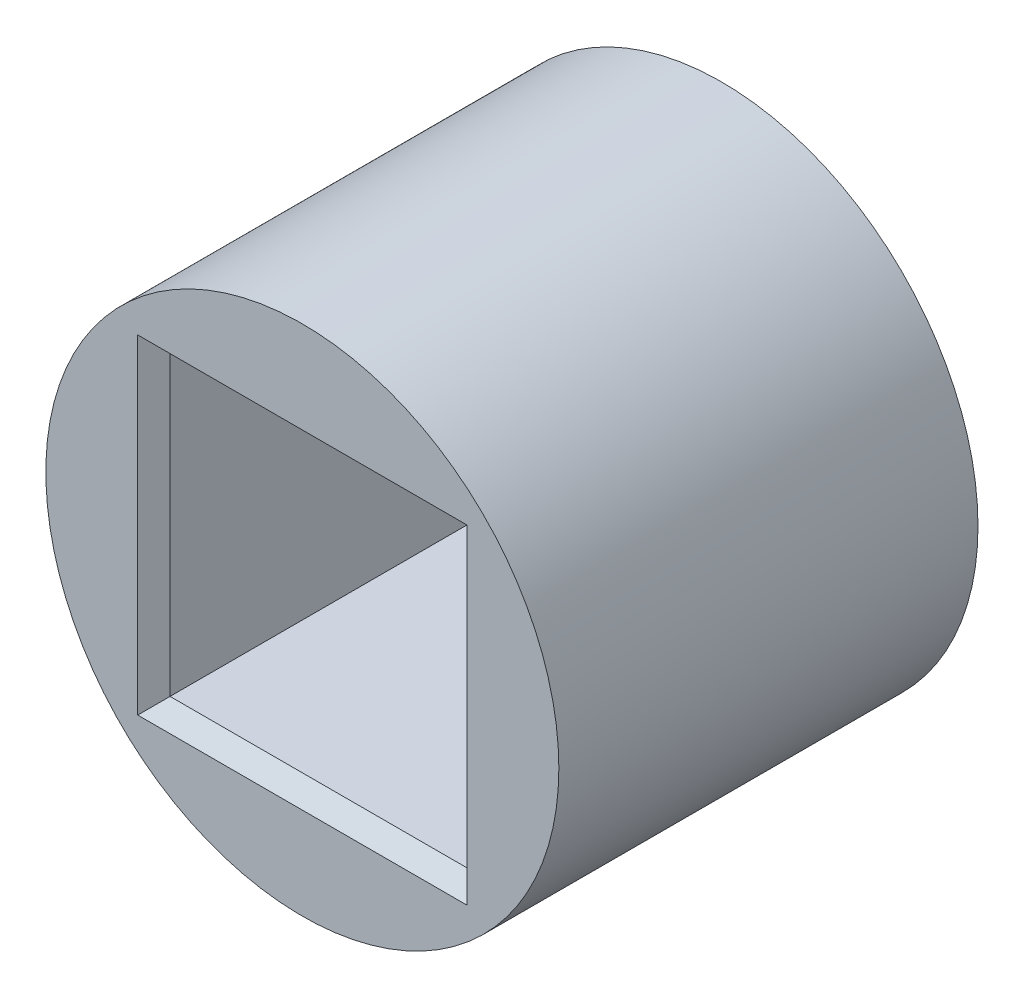
SolidWorks part; units mm, degrees
ref_plane "Front Plane" through (0, 0, 0) normal (0, 0, 1) x (1, 0, 0)
ref_plane "Top Plane" through (0, 0, 0) normal (0, 1, 0) x (1, 0, 0)
ref_plane "Right Plane" through (0, 0, 0) normal (1, 0, 0) x (0, 0, -1)
sketch "Sketch1" plane through (0, 0, 0) normal (0, 0, 1) x (1, 0, 0)
  line L1 (-1.8375, -1.8375) -> (1.8375, -1.8375)
  line L2 (-1.8375, -1.8375) -> (-1.8375, 1.8375)
  line L3 (-1.8375, 1.8375) -> (1.8375, 1.8375)
  line L4 (1.8375, -1.8375) -> (1.8375, 1.8375)
  line L5 (-1.8375, -1.8375) -> (1.8375, 1.8375) construction
  line L6 (-1.8375, 1.8375) -> (1.8375, -1.8375) construction
  circle A0 centre (0, 0) radius 3.175
  dimension "D1" = 6.35
  dimension "D2" = 3.675
  dimension "D3" = 3.675
extrude "Boss-Extrude1" add sketch "Sketch1" along normal blind 5.188
chamfer "Chamfer1" distance 0.2 angle 45 8 edges at (0, -1.8375, 0) (-1.8375, 0, 0) (1.8375, 0, 0) (0, 1.8375, 0) (1.8375, 0, 5.188) (0, 1.8375, 5.188) (0, -1.8375, 5.188) (-1.8375, 0, 5.188)
